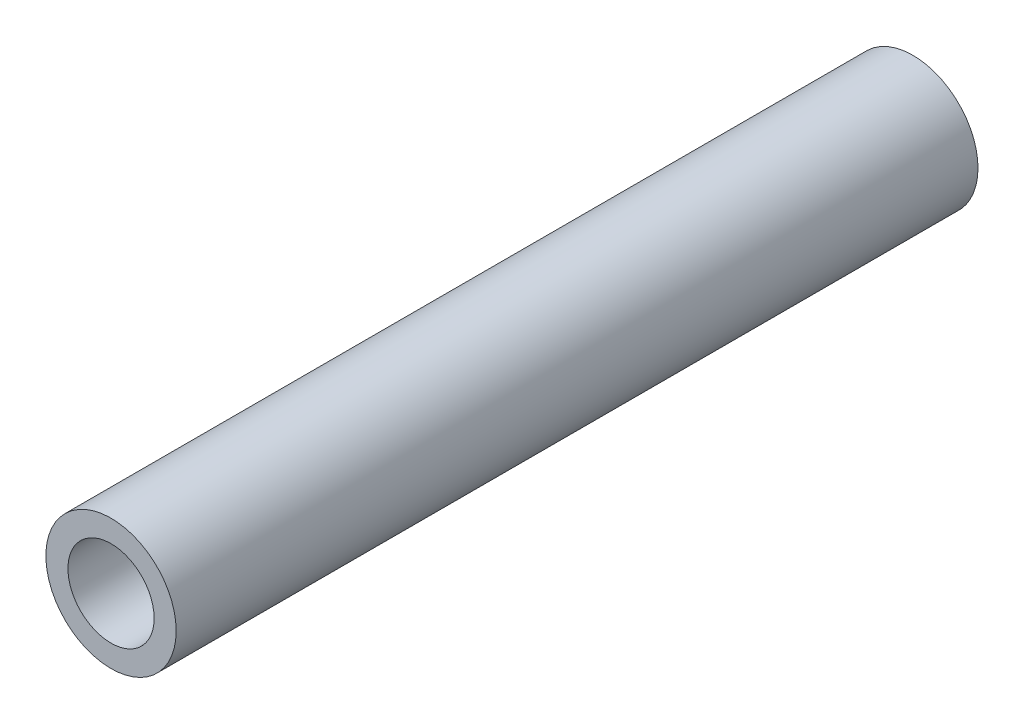
SolidWorks part; units mm, degrees
ref_plane "Front Plane" through (0, 0, 0) normal (0, 0, 1) x (1, 0, 0)
ref_plane "Top Plane" through (0, 0, 0) normal (0, 1, 0) x (1, 0, 0)
ref_plane "Right Plane" through (0, 0, 0) normal (1, 0, 0) x (0, 0, -1)
sketch "Sketch2" plane through (0, 0, 0) normal (0, 0, 1) x (1, 0, 0)
  circle A0 centre (67.6066, -8.5066) radius 4.3
  circle A1 centre (67.6066, -8.5066) radius 6.5
  dimension "D1" = 13
extrude "Boss-Extrude1" add sketch "Sketch2" along normal blind 80
